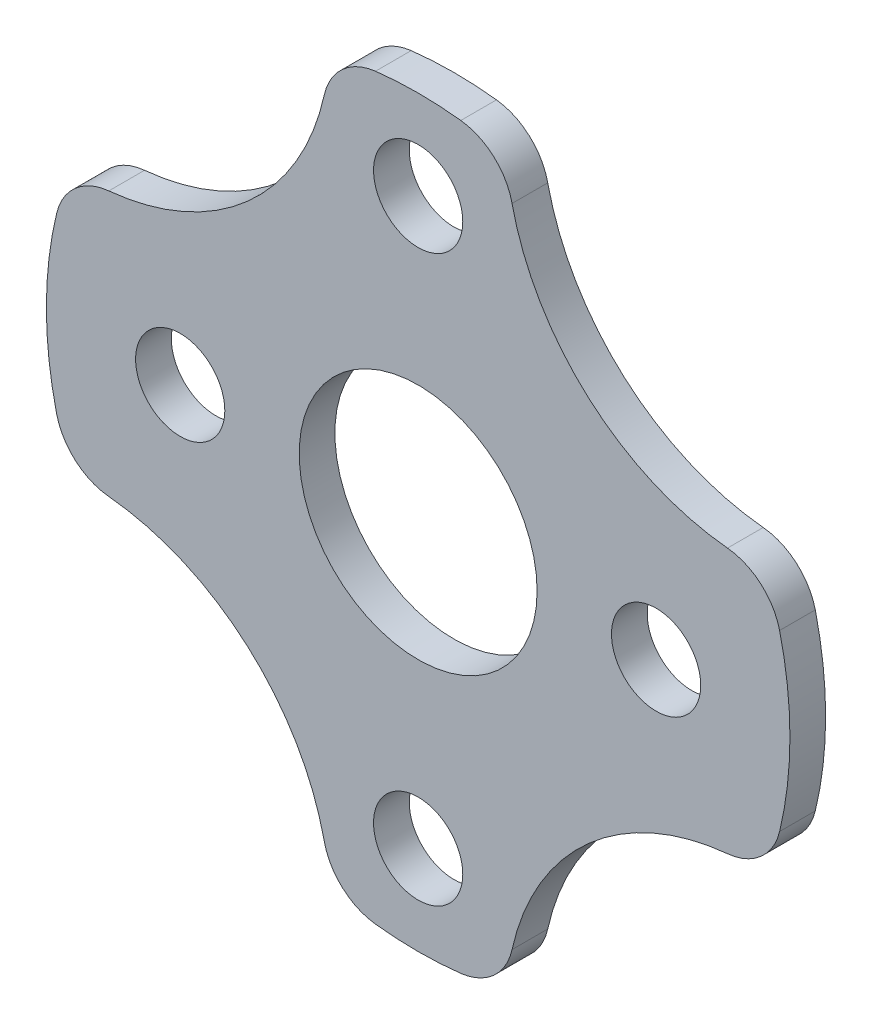
SolidWorks part; units mm, degrees
ref_plane "Alzado" through (0, 0, 0) normal (0, 0, 1) x (1, 0, 0)
ref_plane "Planta" through (0, 0, 0) normal (0, 1, 0) x (1, 0, 0)
ref_plane "Vista lateral" through (0, 0, 0) normal (1, 0, 0) x (0, 0, -1)
sketch "Croquis1" plane through (0, 0, 0) normal (0, 0, 1) x (1, 0, 0)
  line L0 (-75.2493, 7.4839) -> (-50.2493, 7.4839) construction
  line L1 (-62.7493, 19.9839) -> (-62.7493, -5.0161) construction
  circle A0 centre (-62.7493, 7.4839) radius 12.5
  circle A1 centre (-70.7493, 7.4839) radius 1.5
  circle A2 centre (-54.7493, 7.4839) radius 1.5
  circle A3 centre (-62.7493, 16.9839) radius 1.5
  circle A4 centre (-62.7493, -2.0161) radius 1.5
  circle A5 centre (-62.7493, 7.4839) radius 4
  dimension "D1" = 25
  dimension "D2" = 3
  dimension "D3" = 3
  dimension "D6" = 9.5
  dimension "D4" = 16
  dimension "D5" = 8
  dimension "D7" = 19
extrude "Saliente-Extruir1" add sketch "Croquis1" along normal blind 1.2
sketch "Croquis2" plane through (0, 0, 0) normal (0, 0, -1) x (-1, 0, 0)
  line L0 (62.7493, 7.4839) -> (71.5881, 16.3227) construction
  line L1 (71.5881, 16.3227) -> (53.9105, 16.3227) construction
  line L2 (53.9105, 16.3227) -> (53.9105, -1.355) construction
  line L3 (53.9105, -1.355) -> (71.5881, -1.355) construction
  line L4 (71.5881, -1.355) -> (71.5881, 16.3227) construction
  circle A0 centre (62.7493, 7.4839) radius 12.5 construction
  arc A9 (74.4393, 11.9104) -> (65.7276, 19.6239) centre (62.7493, 7.4839) ccw
  arc A10 (74.4393, 3.0574) -> (65.7276, -4.6561) centre (62.7493, 7.4839) cw
  arc A11 (51.0593, 3.0574) -> (59.771, -4.6561) centre (62.7493, 7.4839) ccw
  arc A12 (51.0593, 11.9104) -> (59.771, 19.6239) centre (62.7493, 7.4839) cw
  arc A13 (59.771, -4.6561) -> (51.0593, 3.0574) centre (51.5584, -5.1552) ccw
  arc A14 (51.0593, 11.9104) -> (59.771, 19.6239) centre (51.5584, 20.123) ccw
  arc A15 (74.4393, 11.9104) -> (65.7276, 19.6239) centre (73.9402, 20.123) cw
  arc A16 (65.7276, -4.6561) -> (74.4393, 3.0574) centre (73.9402, -5.1552) cw
extrude "Cortar-Extruir1" cut sketch "Croquis2" against normal blind 10
fillet "Redondeo1" radius 2 8 edges at (-65.7276, 19.6239, 0.6) (-74.4393, 11.9104, 0.6) (-51.0593, 11.9104, 0.6) (-59.771, 19.6239, 0.6) (-59.771, -4.6561, 0.6) (-51.0593, 3.0574, 0.6) (-74.4393, 3.0574, 0.6) (-65.7276, -4.6561, 0.6)
